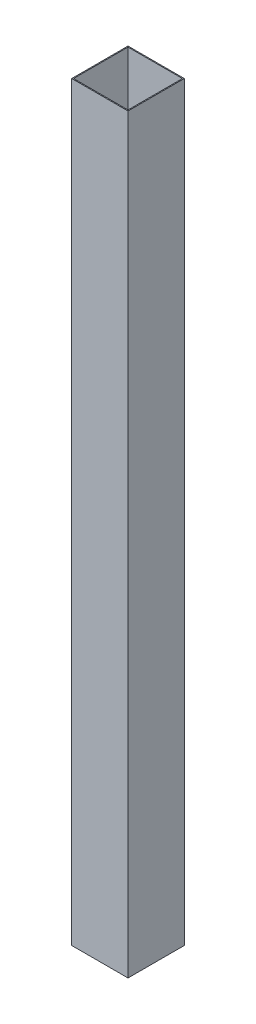
SolidWorks part; units mm, degrees
ref_plane "Front" through (0, 0, 0) normal (0, 0, 1) x (1, 0, 0)
ref_plane "Top" through (0, 0, 0) normal (0, 1, 0) x (1, 0, 0)
ref_plane "Right" through (0, 0, 0) normal (1, 0, 0) x (0, 0, -1)
sketch "Sketch1" plane through (0, 0, 0) normal (0, 1, 0) x (1, 0, 0)
  line L0 (-73.66, 73.66) -> (73.66, 73.66)
  line L1 (-76.2, 76.2) -> (76.2, 76.2)
  line L2 (-76.2, 76.2) -> (-76.2, -76.2)
  line L3 (-76.2, -76.2) -> (76.2, -76.2)
  line L4 (76.2, 76.2) -> (76.2, -76.2)
  line L5 (-76.2, 76.2) -> (76.2, -76.2) construction
  line L6 (-76.2, -76.2) -> (76.2, 76.2) construction
  line L7 (73.66, 73.66) -> (73.66, -73.66)
  line L8 (-73.66, -73.66) -> (73.66, -73.66)
  line L9 (-73.66, 73.66) -> (-73.66, -73.66)
  point P0 (0, 0)
  dimension "D1" = 152.4
  dimension "D2" = 152.4
  dimension "D3" = 2.54
extrude "Boss-Extrude1" add sketch "Sketch1" along normal blind 6604
sketch "Sketch2" plane through (0, 0, 76.2) normal (0, 0, 1) x (1, 0, 0)
  line L0 (76.2, 6604) -> (76.2, 0) construction
  line L1 (-76.2, 6604) -> (76.2, 6604)
  line L2 (-76.2, 6604) -> (-76.2, 2032)
  line L3 (-76.2, 2032) -> (76.2, 2032)
  line L4 (76.2, 6604) -> (76.2, 2032)
  dimension "D1" = 2032
extrude "Cut-Extrude1" cut sketch "Sketch2" against normal through all
sketch "Sketch3" [suppressed] plane through (0, 0, 0) normal (0, -1, 0) x (1, 0, 0)
  line L4 (76.2, -76.2) -> (76.2, 76.2)
  line L5 (76.2, 76.2) -> (-76.2, 76.2)
  line L6 (-76.2, 76.2) -> (-76.2, -76.2)
  line L7 (-76.2, -76.2) -> (76.2, -76.2)
  line L8 (76.2, -76.2) -> (76.2, 76.2)
  line L9 (76.2, 76.2) -> (-76.2, 76.2)
  line L10 (-76.2, 76.2) -> (-76.2, -76.2)
  line L11 (-76.2, -76.2) -> (76.2, -76.2)
  dimension "D1" = 0
extrude "Cut-Extrude2" [suppressed] cut sketch "Sketch3" against normal offset from surface (4572 mm away) 508
